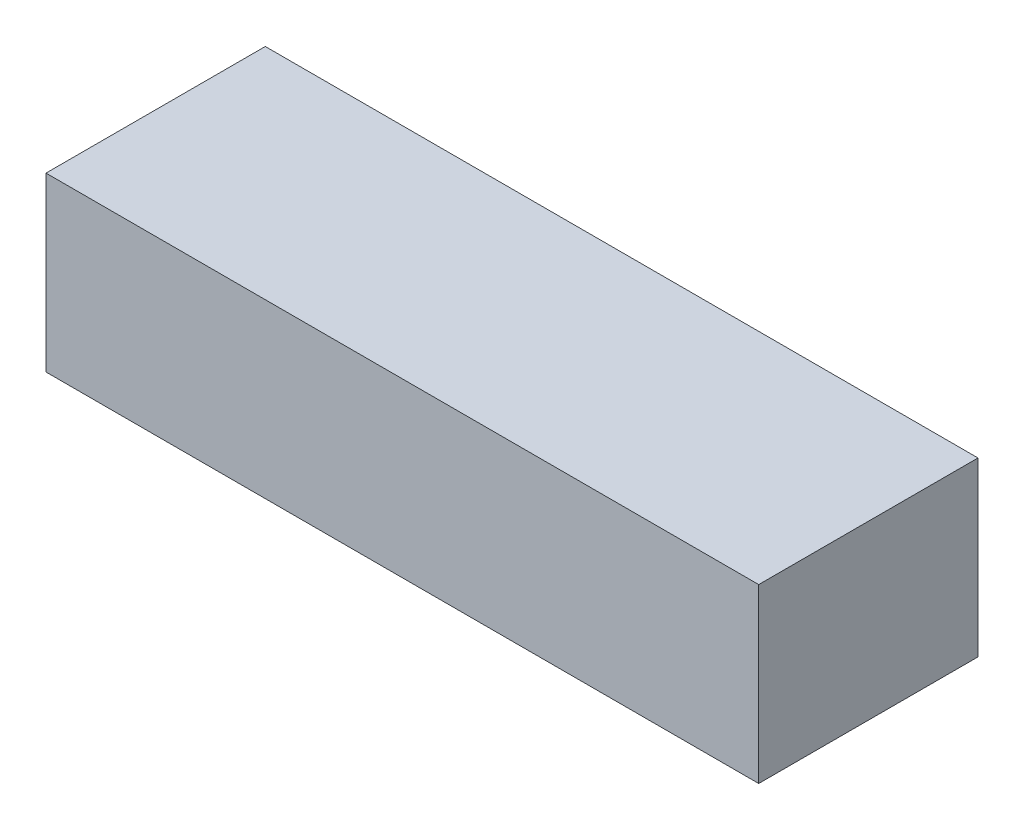
SolidWorks part; units mm, degrees
ref_plane "前视基准面" through (0, 0, 0) normal (0, 0, 1) x (1, 0, 0)
ref_plane "上视基准面" through (0, 0, 0) normal (0, 1, 0) x (1, 0, 0)
ref_plane "右视基准面" through (0, 0, 0) normal (1, 0, 0) x (0, 0, -1)
other "Configuration Table"
sketch "草图1" plane through (0, 0, 0) normal (0, 1, 0) x (1, 0, 0)
  line L0 (0, 0) -> (0, -28)
  line L1 (0, -28) -> (91, -28)
  line L2 (91, -28) -> (91, 0)
  line L3 (91, 0) -> (0, 0)
  dimension "D1" = 28
  dimension "D2" = 91
extrude "凸台-拉伸1" add sketch "草图1" along normal blind 22
